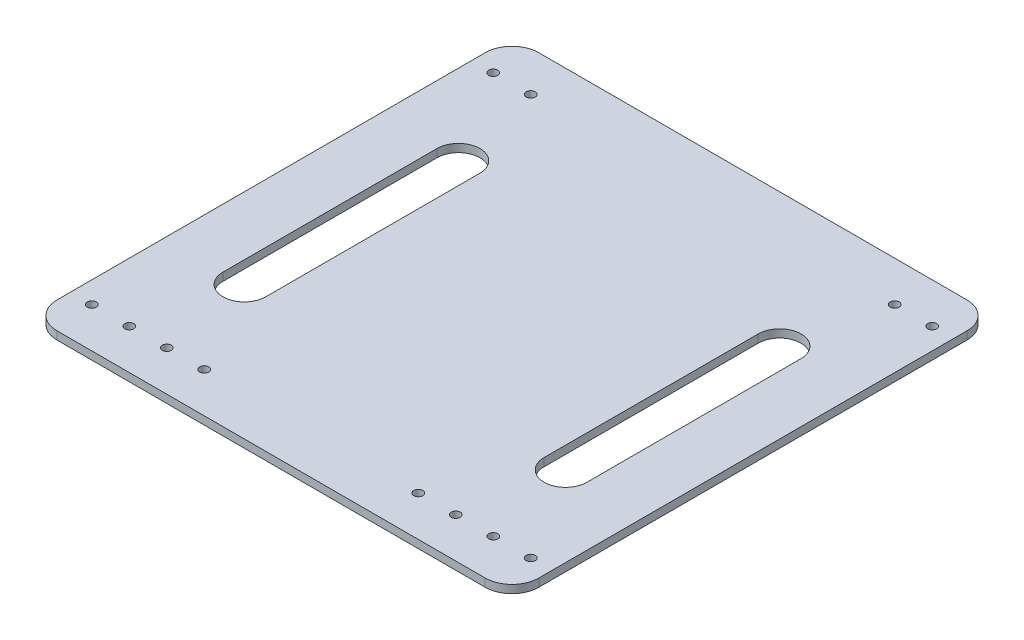
SolidWorks part; units mm, degrees
ref_plane "Front Plane" through (0, 0, 0) normal (0, 0, 1) x (1, 0, 0)
ref_plane "Top Plane" through (0, 0, 0) normal (0, 1, 0) x (1, 0, 0)
ref_plane "Right Plane" through (0, 0, 0) normal (1, 0, 0) x (0, 0, -1)
sketch "Sketch1" plane through (0, 0, 0) normal (0, 1, 0) x (1, 0, 0)
  line L1 (-90, 90) -> (90, 90)
  line L2 (-90, 90) -> (-90, -90)
  line L3 (-90, -90) -> (90, -90)
  line L4 (90, 90) -> (90, -90)
  line L5 (-90, 90) -> (90, -90) construction
  line L6 (-90, -90) -> (90, 90) construction
  point P0 (0, 0)
  dimension "D1" = 180
  dimension "D2" = 180
extrude "Boss-Extrude1" add sketch "Sketch1" along normal blind 3
fillet "Fillet1" radius 10 4 edges at (-90, 1.5, -90) (-90, 1.5, 90) (90, 1.5, -90) (90, 1.5, 90)
sketch "Sketch2" plane through (0, 3, 0) normal (0, 1, 0) x (1, 0, 0)
  circle A0 centre (-82, 75) radius 1.7
  circle A1 centre (-68, 75) radius 1.7
  circle A2 centre (68, 75) radius 1.7
  circle A3 centre (82, 75) radius 1.7
  circle A4 centre (-82, -75) radius 1.7
  circle A5 centre (-68, -75) radius 1.7
  circle A6 centre (68, -75) radius 1.7
  circle A7 centre (82, -75) radius 1.7
  circle A32 centre (-54, -75) radius 1.7
  circle A33 centre (54, -75) radius 1.7
  circle A34 centre (-40, -75) radius 1.7
  circle A35 centre (40, -75) radius 1.7
  dimension "D1" = 3.4
  dimension "D11" = 14
  dimension "D18" = 14
  dimension "D19" = 14
  dimension "D20" = 14
  dimension "D2" = 14
  dimension "D3" = 14
  dimension "D4" = 82
  dimension "D5" = 82
  dimension "D6" = 75
  dimension "D7" = 75
extrude "Cut-Extrude1" cut sketch "Sketch2" against normal up to surface (3 mm away) up to face at (0, 0, 0)
sketch "Sketch3" plane through (0, 3, 0) normal (0, 1, 0) x (1, 0, 0)
  line L0 (-60, 40) -> (-60, -40) construction
  line L1 (-52, 40) -> (-52, -40)
  line L2 (-68, 40) -> (-68, -40)
  line L3 (60, 40) -> (60, -40) construction
  line L4 (68, 40) -> (68, -40)
  line L5 (52, 40) -> (52, -40)
  arc A0 (-52, 40) -> (-68, 40) centre (-60, 40) ccw
  arc A1 (-68, -40) -> (-52, -40) centre (-60, -40) ccw
  arc A2 (68, 40) -> (52, 40) centre (60, 40) ccw
  arc A3 (52, -40) -> (68, -40) centre (60, -40) ccw
  point P2 (-60, 0)
  point P9 (60, 0)
  point P17 (19.6857, -3.0988)
  dimension "D1" = 80
  dimension "D2" = 16
  dimension "D3" = 60
  dimension "D4" = 60
extrude "Cut-Extrude2" cut sketch "Sketch3" against normal through all
